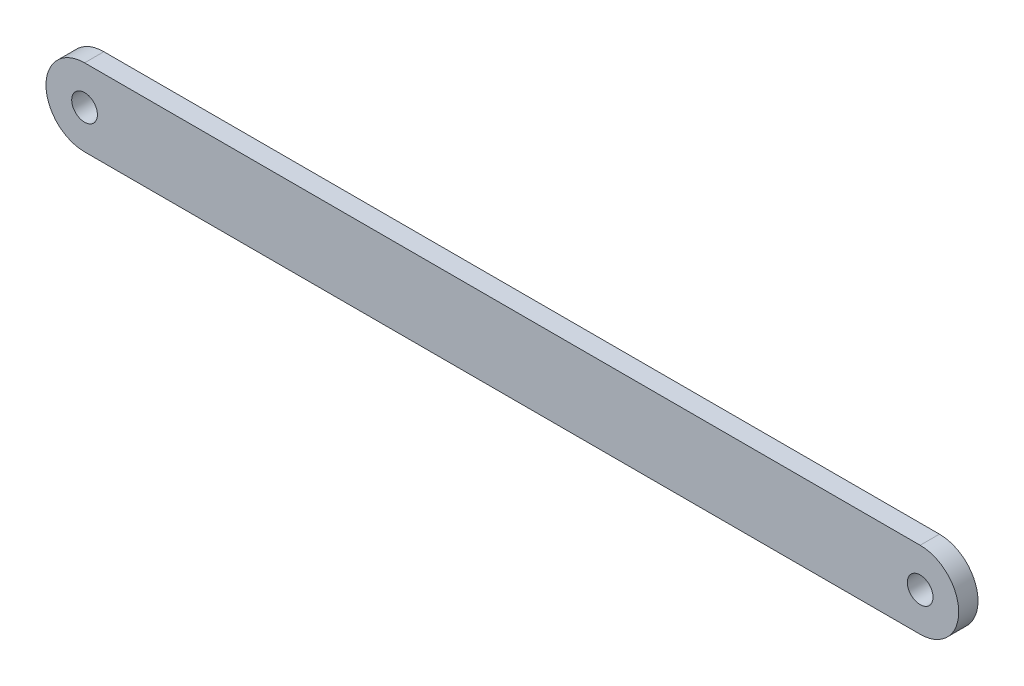
SolidWorks part; units mm, degrees
ref_plane "Front Plane" through (0, 0, 0) normal (0, 0, 1) x (1, 0, 0)
ref_plane "Top Plane" through (0, 0, 0) normal (0, 1, 0) x (1, 0, 0)
ref_plane "Right Plane" through (0, 0, 0) normal (1, 0, 0) x (0, 0, -1)
sketch "Sketch1" plane through (0, 0, 0) normal (0, 0, 1) x (1, 0, 0)
  line L0 (-35.3127, 0) -> (94.6873, 0) construction
  line L1 (-35.3127, 6) -> (94.6873, 6)
  line L2 (-35.3127, -6) -> (94.6873, -6)
  arc A0 (-35.3127, 6) -> (-35.3127, -6) centre (-35.3127, 0) ccw
  arc A1 (94.6873, -6) -> (94.6873, 6) centre (94.6873, 0) ccw
  circle A2 centre (-35.3127, 0) radius 2
  circle A3 centre (94.6873, 0) radius 2
  point P3 (29.6873, 0)
  dimension "D3" = 4
  dimension "D4" = 4
  dimension "D1" = 130
  dimension "D2" = 12
extrude "Boss-Extrude3" add sketch "Sketch1" along normal blind 3
